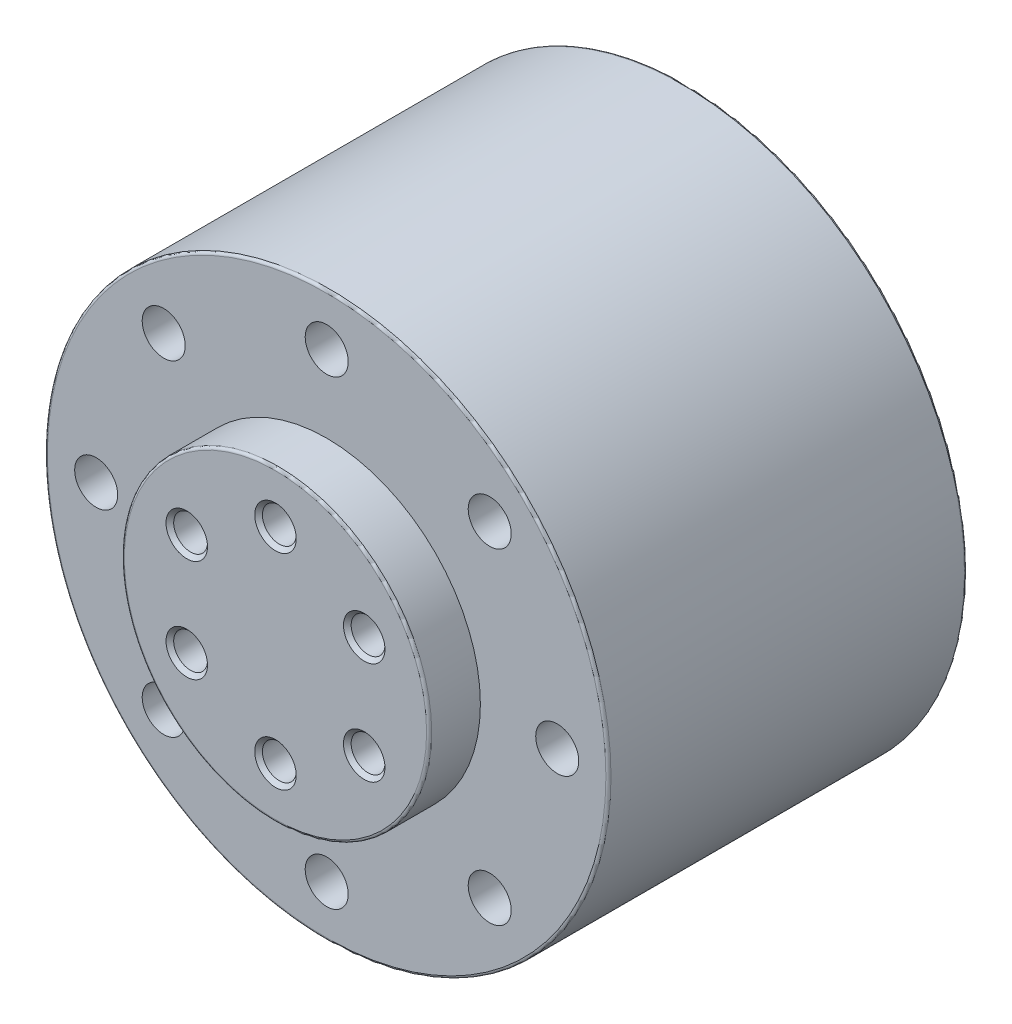
SolidWorks part; units mm, degrees
ref_plane "前视基准面" through (0, 0, 0) normal (0, 0, 1) x (1, 0, 0)
ref_plane "上视基准面" through (0, 0, 0) normal (0, 1, 0) x (1, 0, 0)
ref_plane "右视基准面" through (0, 0, 0) normal (1, 0, 0) x (0, 0, -1)
other "Configuration Table"
sketch "草图1" plane through (0, 0, 0) normal (0, 0, 1) x (1, 0, 0)
  circle A0 centre (0, 0) radius 27.5
  dimension "D1" = 55
extrude "凸台-拉伸1" add sketch "草图1" along normal blind 35
sketch "草图2" plane through (0, 0, 35) normal (0, 0, 1) x (1, 0, 0)
  circle A0 centre (0, 0) radius 15
  dimension "D1" = 30
extrude "凸台-拉伸2" add sketch "草图2" along normal blind 5
sketch "草图3" plane through (0, 0, 0) normal (0, 0, -1) x (-1, 0, 0)
  circle A0 centre (0, 0) radius 22.5 construction
  circle A1 centre (0, 22.5) radius 2.5
  circle A2 centre (15.9099, 15.9099) radius 2.5
  circle A3 centre (22.5, 0) radius 2.5
  circle A4 centre (15.9099, -15.9099) radius 2.5
  circle A5 centre (0, -22.5) radius 2.5
  circle A6 centre (-15.9099, -15.9099) radius 2.5
  circle A7 centre (-22.5, 0) radius 2.5
  circle A8 centre (-15.9099, 15.9099) radius 2.5
  point P21 (0, 0)
  dimension "D1" = 45
  dimension "D2" = 5
  dimension "D3" = 8
hole_wizard "M5 螺纹孔1" positions "3D草图1" profile "草图4" tap size "M5" standard "GB" end condition up to next
sketch3d "3D草图1"
  point P0 (0, 22.5, 0)
  point P3 (-15.9099, 15.9099, 0)
  point P6 (-22.5, 0, 0)
  point P9 (-15.9099, -15.9099, 0)
  point P12 (0, -22.5, 0)
  point P15 (15.9099, -15.9099, 0)
  point P18 (22.5, 0, 0)
  point P21 (15.9099, 15.9099, 0)
sketch "草图4" plane through (0, 22.5, 0) normal (1, 0, 0) x (0, 1, 0)
  line L0 (0, 0) -> (0, 35)
  line L1 (0, 35) -> (2.1, 35)
  line L2 (2.1, 35) -> (2.1, 0.425)
  line L3 (2.1, 0.425) -> (2.525, 0)
  line L5 (2.525, 0) -> (0, 0)
  line L6 (-2.1, 0.425) -> (-2.525, 0) construction
  line L11 (0, -6.35) -> (0, 107.95) construction
  dimension "通孔螺纹孔钻头直径" = 4.2
  dimension "通孔螺纹孔钻头深度" = 35
  dimension "近端锥形沉头孔直径" = 5.05
  dimension "近端锥形沉头孔角度" = 90
cosmetic thread "孔螺蚊线23" parameters "D1"=10, "D2"=5.2
cosmetic thread "孔螺蚊线24" parameters "D1"=10, "D2"=5.2
cosmetic thread "孔螺蚊线25" parameters "D1"=10, "D2"=5.2
cosmetic thread "孔螺蚊线26" parameters "D1"=10, "D2"=5.2
cosmetic thread "孔螺蚊线27" parameters "D1"=10, "D2"=5.2
cosmetic thread "孔螺蚊线28" parameters "D1"=10, "D2"=5.2
cosmetic thread "孔螺蚊线29" parameters "D1"=10, "D2"=5.2
cosmetic thread "孔螺蚊线30" parameters "D1"=10, "D2"=5.2
sketch "草图5" plane through (0, 0, 40) normal (0, 0, 1) x (1, 0, 0)
  circle A0 centre (0, 0) radius 10 construction
  circle A1 centre (0, 10) radius 2
  circle A2 centre (8.6603, 5) radius 2
  circle A3 centre (8.6603, -5) radius 2
  circle A4 centre (0, -10) radius 2
  circle A5 centre (-8.6603, -5) radius 2
  circle A6 centre (-8.6603, 5) radius 2
  point P17 (0, 0)
  dimension "D1" = 20
  dimension "D2" = 4
  dimension "D3" = 6
hole_wizard "M4 螺纹孔1" positions "3D草图2" profile "草图6" tap size "M4" standard "GB"
sketch3d "3D草图2"
  point P0 (0, 10, 40)
  point P3 (8.6603, 5, 40)
  point P6 (8.6603, -5, 40)
  point P9 (0, -10, 40)
  point P12 (-8.6603, -5, 40)
  point P15 (-8.6603, 5, 40)
sketch "草图6" plane through (0, 10, 40) normal (1, 0, 0) x (0, -1, 0)
  line L0 (0, 0) -> (0, 11.0914)
  line L1 (0, 11.0914) -> (1.65, 10.1)
  line L2 (1.65, 10.1) -> (1.65, 0.375)
  line L3 (1.65, 0.375) -> (2.025, 0)
  line L5 (2.025, 0) -> (0, 0)
  line L6 (-1.65, 0.375) -> (-2.025, 0) construction
  line L10 (0, 11.0914) -> (-1.65, 10.1) construction
  line L11 (0, -6.35) -> (0, 107.95) construction
  dimension "螺纹孔钻头直径" = 3.3
  dimension "螺纹孔钻头深度" = 10.1
  dimension "近端锥形沉头孔直径" = 4.05
  dimension "近端锥形沉头孔角度" = 90
  dimension "导头角度" = 118
cosmetic thread "孔螺蚊线9" parameters "D1"=8, "D2"=4
cosmetic thread "孔螺蚊线10" parameters "D1"=8, "D2"=4
cosmetic thread "孔螺蚊线11" parameters "D1"=8, "D2"=4
cosmetic thread "孔螺蚊线12" parameters "D1"=8, "D2"=4
cosmetic thread "孔螺蚊线13" parameters "D1"=8, "D2"=4
cosmetic thread "孔螺蚊线14" parameters "D1"=8, "D2"=4
fillet "圆角1" radius 0.25 3 edges at (15, 0, 40) (27.5, 0, 35) (27.5, 0, 0)
ref_plane "基准面1" through (0, 0, 20) normal (0, 0, -1) x (-1, 0, 0)
